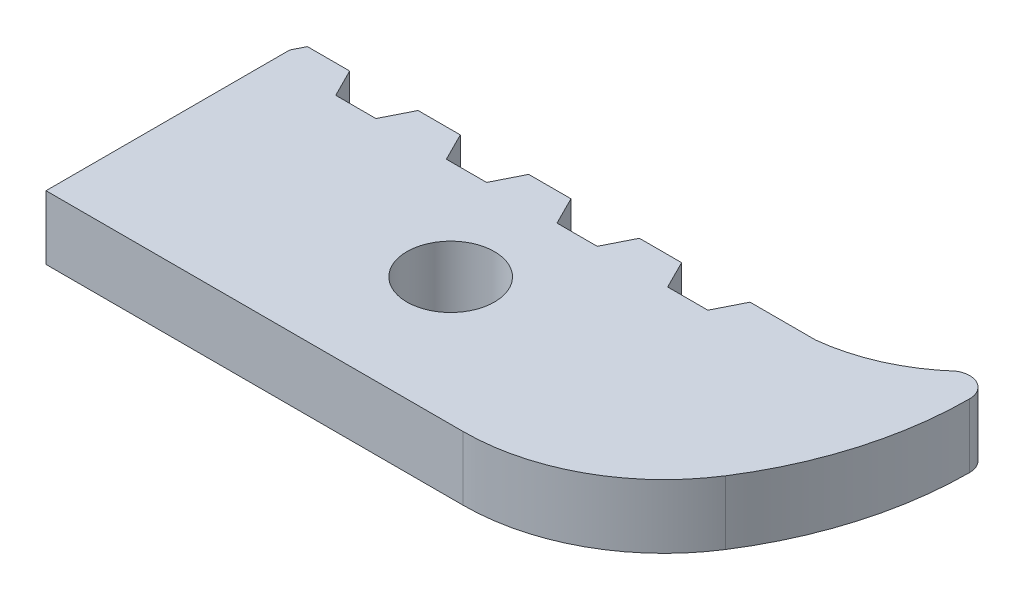
SolidWorks part; units mm, degrees
material "PET"
ref_plane "Front" through (0, 0, 0) normal (0, 0, 1) x (1, 0, 0)
ref_plane "Top" through (0, 0, 0) normal (0, 1, 0) x (1, 0, 0)
ref_plane "Right" through (0, 0, 0) normal (1, 0, 0) x (0, 0, -1)
sketch "Sketch1" plane through (0, 0, 0) normal (0, 1, 0) x (1, 0, 0)
  line L1 (-62.8447, 8.7002) -> (13.3553, 8.7002)
  line L3 (-62.8447, -3.9998) -> (13.3553, -3.9998)
  line L5 (-62.8447, 8.7002) -> (13.3553, -3.9998) construction
  line L6 (-62.8447, -3.9998) -> (13.3553, 8.7002) construction
  arc A0 (-62.8447, 8.7002) -> (-62.8447, -3.9998) centre (-62.8447, 2.3502) ccw
  arc A2 (13.3553, 8.7002) -> (13.3553, -3.9998) centre (13.3553, 2.3502) cw
  point P4 (-24.7447, 2.3502)
  dimension "D1" = 76.2
  dimension "D2" = 12.7
extrude "Boss-Extrude1" add sketch "Sketch1" along normal blind 3.175
sketch "Sketch2" plane through (0, 3.175, 0) normal (0, 1, 0) x (1, 0, 0)
  circle A0 centre (-62.8447, 2.3502) radius 2.175
  circle A1 centre (-31.0947, 2.3502) radius 2.175
  circle A2 centre (1.5553, 2.3502) radius 2.175
  arc A3 (13.3553, -3.9998) -> (13.3553, 8.7002) centre (13.3553, 2.3502) ccw construction
  dimension "D1" = 31.75
  dimension "D2" = 4.35
  dimension "D3" = 4.35
  dimension "D4" = 4.35
  dimension "D5" = 11.8
extrude "Cut-Extrude2" cut sketch "Sketch2" against normal blind 6.35
sketch "Sketch3" plane through (0, 3.175, 0) normal (0, 1, 0) x (1, 0, 0)
  line L2 (13.3553, 8.7002) -> (13.3553, 2.3502)
  line L7 (19.7053, 2.3502) -> (19.7053, 9.9994)
  line L8 (19.7053, 2.3502) -> (13.3553, 2.3502)
  arc A0 (13.3553, -3.9998) -> (13.3553, 8.7002) centre (13.3553, 2.3502) ccw construction
  arc A2 (19.7053, 9.9994) -> (18.1741, 10.8466) centre (18.7053, 9.9994) ccw
  arc A3 (18.1741, 10.8466) -> (13.3553, 8.7002) centre (12.37, 17.3945) cw
  point P4 (25.0274, 5.3951)
  dimension "D1" = 1
  dimension "D2" = 7.6492
  dimension "D3" = 6.35
  dimension "D5" = 1.75
  dimension "D6" = 8.75
  dimension "D4" = 6.35
extrude "Boss-Extrude2" add sketch "Sketch3" against normal up to vertex (3.175 mm away)
sketch "Sketch4" plane through (0, 3.175, 0) normal (0, 1, 0) x (1, 0, 0)
  line L1 (19.7053, 9.9994) -> (19.7053, -6.0006)
  line L2 (19.7053, -6.0006) -> (9.2053, -6.0006)
  arc A3 (19.7053, 9.9994) -> (9.2053, -6.0006) centre (2.2054, 10.0384) cw
  arc A4 (19.7053, 9.9994) -> (18.1741, 10.8466) centre (18.7053, 9.9994) ccw construction
  dimension "D1" = 16
  dimension "D3" = 17.5
  dimension "D2" = 10.5
extrude "Cut-Extrude3" cut sketch "Sketch4" against normal blind 10
fillet "Fillet1" radius 10 1 edges at (12.6542, 1.5875, 3.9998)
sketch "Sketch5" plane through (0, 3.175, 0) normal (0, 1, 0) x (1, 0, 0)
  line L0 (-4.3147, 8.7002) -> (-0.9147, 8.7002)
  line L1 (13.3553, 8.7002) -> (-62.8447, 8.7002) construction
  line L3 (-9.8147, 8.7002) -> (-9.1147, 7.306)
  line L4 (-9.1147, 7.306) -> (-7.1147, 7.306)
  line L5 (-7.1147, 7.306) -> (-6.4147, 8.7002)
  line L14 (-4.3147, 8.7002) -> (-3.6147, 7.306)
  line L18 (-9.8147, 8.7002) -> (-6.4147, 8.7002)
  line L19 (-3.6147, 7.306) -> (-1.6147, 7.306)
  line L20 (-1.6147, 7.306) -> (-0.9147, 8.7002)
  line L21 (1.1853, 8.7002) -> (4.5853, 8.7002)
  line L22 (1.1853, 8.7002) -> (1.8853, 7.306)
  line L23 (1.8853, 7.306) -> (3.8853, 7.306)
  line L24 (3.8853, 7.306) -> (4.5853, 8.7002)
  line L25 (6.6853, 8.7002) -> (10.0853, 8.7002)
  line L26 (6.6853, 8.7002) -> (7.3853, 7.306)
  line L27 (7.3853, 7.306) -> (9.3853, 7.306)
  line L28 (9.3853, 7.306) -> (10.0853, 8.7002)
  line L29 (-15.3147, 8.7002) -> (-11.9147, 8.7002)
  line L30 (-15.3147, 8.7002) -> (-14.6147, 7.306)
  line L31 (-14.6147, 7.306) -> (-12.6147, 7.306)
  line L32 (-12.6147, 7.306) -> (-11.9147, 8.7002)
  line L33 (-20.8147, 8.7002) -> (-17.4147, 8.7002)
  line L34 (-20.8147, 8.7002) -> (-20.1147, 7.306)
  line L35 (-20.1147, 7.306) -> (-18.1147, 7.306)
  line L36 (-18.1147, 7.306) -> (-17.4147, 8.7002)
  line L37 (-26.3147, 8.7002) -> (-22.9147, 8.7002)
  line L38 (-26.3147, 8.7002) -> (-25.6147, 7.306)
  line L39 (-25.6147, 7.306) -> (-23.6147, 7.306)
  line L40 (-23.6147, 7.306) -> (-22.9147, 8.7002)
  dimension "D1" = 4
  dimension "D2" = 4
  dimension "D3" = 2
  dimension "D4" = 1.56
  dimension "D5" = 1.56
extrude "Cut-Extrude4" cut sketch "Sketch5" against normal blind 10
sketch "Sketch6" plane through (0, 3.175, 0) normal (0, 1, 0) x (1, 0, 0)
  line L0 (-62.8447, -3.9998) -> (8.5254, -3.9998) construction
  line L1 (-69.1947, 15.0502) -> (-12.2095, 15.0502)
  line L2 (-69.1947, 15.0502) -> (-69.1947, -10.3498)
  line L3 (-69.1947, -10.3498) -> (-12.2095, -10.3498)
  line L4 (-12.2095, 15.0502) -> (-12.2095, -10.3498)
  arc A1 (-62.8447, 8.7002) -> (-62.8447, -3.9998) centre (-62.8447, 2.3502) ccw construction
  dimension "D4" = 6.35
  dimension "D1" = 25.4
  dimension "D2" = 56.9852
  dimension "D3" = 6.35
extrude "Cut-Extrude5" cut sketch "Sketch6" against normal through all
